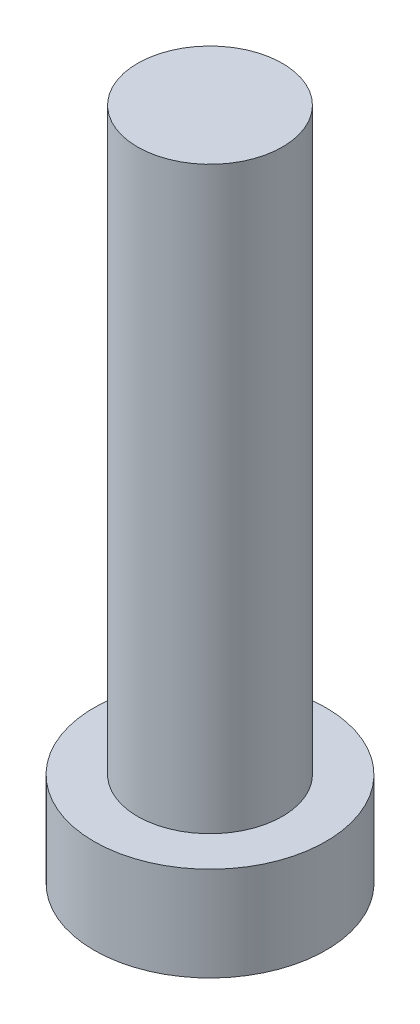
SolidWorks part; units mm, degrees
ref_plane "前视基准面" through (0, 0, 0) normal (0, 0, 1) x (1, 0, 0)
ref_plane "上视基准面" through (0, 0, 0) normal (0, 1, 0) x (1, 0, 0)
ref_plane "右视基准面" through (0, 0, 0) normal (1, 0, 0) x (0, 0, -1)
sketch "草图1" plane through (0, 0, 0) normal (0, 1, 0) x (1, 0, 0)
  circle A0 centre (0, 0) radius 1.6
  dimension "D1" = 3.2
extrude "凸台-拉伸1" add sketch "草图1" along normal blind 1.3
sketch "草图2" plane through (0, 1.3, 0) normal (0, 1, 0) x (1, 0, 0)
  circle A0 centre (0, 0) radius 1
  dimension "D1" = 2
extrude "凸台-拉伸2" add sketch "草图2" along normal blind 8
